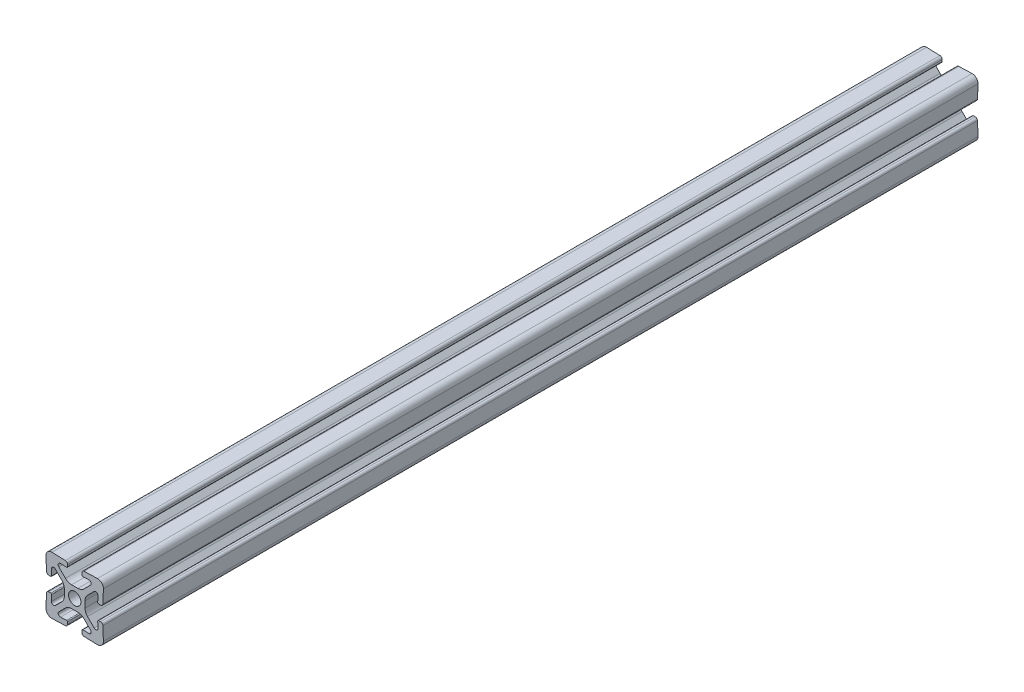
SolidWorks part; units mm, degrees
ref_plane "Front Plane" through (0, 0, 0) normal (0, 0, 1) x (1, 0, 0)
ref_plane "Top Plane" through (0, 0, 0) normal (0, 1, 0) x (1, 0, 0)
ref_plane "Right Plane" through (0, 0, 0) normal (1, 0, 0) x (0, 0, -1)
sketch "Sketch1" plane through (0, 0, 0) normal (0, 0, 1) x (1, 0, 0)
  line L0 (0, 0) -> (0, 10) construction
  line L1 (0, 0) -> (10, 0) construction
  line L2 (0, 0) -> (-10, 10) construction
  line L3 (-7.9302, 9.9988) -> (-3.2721, 9.8361)
  line L4 (-10, 10) -> (0, 10) construction
  line L6 (-2.8352, 8.0198) -> (-4.953, 8.0937)
  line L10 (0, 3.6) -> (-1.1022, 3.6)
  line L11 (-3.2236, 4.4787) -> (-5.5244, 6.7796)
  line L24 (0, 0) -> (-10, 0) construction
  line L25 (-10, 0) -> (0, 0) construction
  line L26 (0, 0) -> (0, -10) construction
  line L27 (-10, -10) -> (-10, 10) construction
  line L28 (0, 10) -> (10, 10) construction
  line L29 (-2.5249, 8.3091) -> (-2.5005, 9.0087)
  line L30 (-10, -10) -> (10, -10) construction
  arc A0 (-9.4142, 9.4142) -> (-7.9302, 9.9988) centre (-8, 8) cw
  arc A5 (-3.2721, 9.8361) -> (-2.5005, 9.0087) centre (-3.3, 9.0366) cw
  arc A6 (-1.1022, 3.6) -> (-3.2236, 4.4787) centre (-1.1022, 6.6) cw
  circle A16 centre (0, 0) radius 2.15
  arc A18 (-5.5244, 6.7796) -> (-4.953, 8.0937) centre (-4.9799, 7.3241) cw
  arc A20 (-2.8352, 8.0198) -> (-2.5249, 8.3091) centre (-2.8247, 8.3196) ccw
  point P15 (0, 0)
  point P42 (-2.3449, 3.6)
  point P80 (-10, 0)
  point P85 (0, -10)
  point P88 (0, -10)
  dimension "D11" = 2
  dimension "D15" = 3
  dimension "Center Hole Diameter" = 4.3
  dimension "D7" = 0.8
  dimension "D8" = 0.3
  dimension "D4" = 0.7701
  dimension "D1" = 45
  dimension "D2" = 2
  dimension "Rail Width" = 20
  dimension "T-Slot Depth" = 6.4
  dimension "D9" = 1.8
  dimension "Rail Height" = 20
  dimension "D23" = 7.2
  dimension "D5" = 11.5
  dimension "T-Slot Width" = 5
  dimension "D3" = 1.775
  dimension "D6" = 9.9598
sketch "Sketch2" plane through (0, 0, 0) normal (1, 0, 0) x (0, 0, -1)
  line L0 (-152.4, 0) -> (152.4, 0)
  line L1 (-152.4, -10) -> (-152.4, 10)
  line L2 (0, 0) -> (0, 10) construction
  line L3 (0, 0) -> (0, 10) construction
  line L4 (152.4, -10) -> (152.4, 10)
  point P0 (-122.4, 0)
  point P3 (0, 0)
  point P7 (122.4, 0)
  point P11 (-152.4, 0)
  point P14 (152.4, 0)
  dimension "D1" = 30
  dimension "Representative Length" = 304.8
sketch "Sketch3" plane through (0, 0, 0) normal (0, 0, 1) x (1, 0, 0)
  line L0 (-2.5249, 8.3091) -> (-2.5005, 9.0087) construction
  line L1 (0, 0) -> (-10, 10) construction
  line L2 (0, 0) -> (-10, 10) construction
  line L5 (-7.9302, 9.9988) -> (-3.2721, 9.8361) construction
  line L6 (-2.8352, 8.0198) -> (-4.953, 8.0937) construction
  line L17 (-2.5249, 8.3091) -> (-2.5005, 9.0087)
  line L19 (-2.8352, 8.0198) -> (-4.953, 8.0937)
  line L20 (0, 0) -> (0, 10) construction
  line L21 (-3.6, 0) -> (-2.15, 0)
  line L22 (-3.6, 0) -> (-3.6, 1.1022)
  line L23 (-4.4787, 3.2236) -> (-6.7796, 5.5244)
  line L42 (-3.2236, 4.4787) -> (-5.5244, 6.7796) construction
  line L43 (0, 3.6) -> (-1.1022, 3.6) construction
  line L44 (-7.9302, 9.9988) -> (-3.2721, 9.8361)
  line L47 (-3.2236, 4.4787) -> (-5.5244, 6.7796)
  line L48 (0, 3.6) -> (-1.1022, 3.6)
  line L59 (0, 3.6) -> (0, 2.15)
  line L60 (-9.9988, 7.9302) -> (-9.8361, 3.2721)
  line L61 (-8.0198, 2.8352) -> (-8.0937, 4.953)
  line L62 (-8.3091, 2.5249) -> (-9.0087, 2.5005)
  arc A0 (-7.9302, 9.9988) -> (-9.4142, 9.4142) centre (-8, 8) ccw construction
  arc A1 (-2.8352, 8.0198) -> (-2.5249, 8.3091) centre (-2.8247, 8.3196) ccw construction
  arc A3 (-2.8352, 8.0198) -> (-2.5249, 8.3091) centre (-2.8247, 8.3196) ccw
  arc A5 (-7.9302, 9.9988) -> (-9.9988, 7.9302) centre (-8, 8) ccw
  circle A13 centre (0, 0) radius 2.15 construction
  arc A14 (0, 2.15) -> (-2.15, 0) centre (0, 0) ccw
  arc A15 (-4.4787, 3.2236) -> (-3.6, 1.1022) centre (-6.6, 1.1022) cw
  arc A16 (-8.0937, 4.953) -> (-6.7796, 5.5244) centre (-7.3241, 4.9799) cw
  arc A17 (-9.0087, 2.5005) -> (-9.8361, 3.2721) centre (-9.0366, 3.3) cw
  arc A18 (-8.0198, 2.8352) -> (-8.3091, 2.5249) centre (-8.3196, 2.8247) cw
  arc A36 (-2.5005, 9.0087) -> (-3.2721, 9.8361) centre (-3.3, 9.0366) ccw construction
  arc A38 (-4.953, 8.0937) -> (-5.5244, 6.7796) centre (-4.9799, 7.3241) ccw construction
  arc A39 (-3.2236, 4.4787) -> (-1.1022, 3.6) centre (-1.1022, 6.6) ccw construction
  arc A41 (-2.5005, 9.0087) -> (-3.2721, 9.8361) centre (-3.3, 9.0366) ccw
  arc A43 (-4.953, 8.0937) -> (-5.5244, 6.7796) centre (-4.9799, 7.3241) ccw
  arc A44 (-3.2236, 4.4787) -> (-1.1022, 3.6) centre (-1.1022, 6.6) ccw
extrude "Boss-Extrude1" add sketch "Sketch3" along normal mid plane 304.8
pattern_circular "CirPattern1" count 4 over 360 about axis through (0, 0, 0) along (0, 0, 1) of "Boss-Extrude1"
ref_plane "Contact Plane 1" through (0, 10, 0) normal (0, 1, 0) x (1, 0, 0)
ref_plane "Contact Plane 2" through (10, 0, 0) normal (1, 0, 0) x (0, 0, -1)
ref_plane "Contact Plane 3" through (0, -10, 0) normal (0, -1, 0) x (-1, 0, 0)
ref_plane "Contact Plane 4" through (-10, 0, 0) normal (-1, 0, 0) x (0, 0, 1)
equation "\"D1@Sketch2\"=\"Rail Width@Sketch1\"*1.5"
equation "\"D1@Boss-Extrude1\" = \"Representative Length@Sketch2\""
